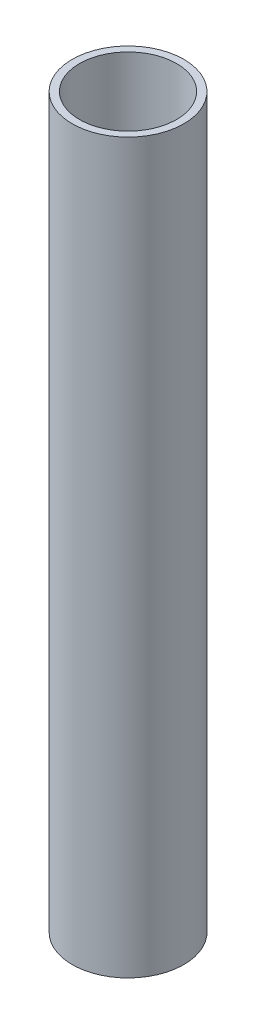
SolidWorks part; units mm, degrees
ref_plane "Plan1" through (0, 0, 0) normal (0, 0, 1) x (1, 0, 0)
ref_plane "Plan2" through (0, 0, 0) normal (0, 1, 0) x (1, 0, 0)
ref_plane "Plan3" through (0, 0, 0) normal (1, 0, 0) x (0, 0, -1)
sketch "Esquisse1" plane through (0, 0, 0) normal (0, 0, 1) x (1, 0, 0)
  line L0 (0, 0) -> (0, 110) construction
  line L1 (10, 0) -> (11.5, 0)
  line L2 (11.5, 0) -> (11.5, 150)
  line L3 (11.5, 150) -> (10, 150)
  line L4 (10, 150) -> (10, 0)
  dimension "D1" = 20
  dimension "D2" = 11.5
  dimension "D3" = 150
revolve "Base-Révolution" add sketch "Esquisse1" angle 360 about L0
